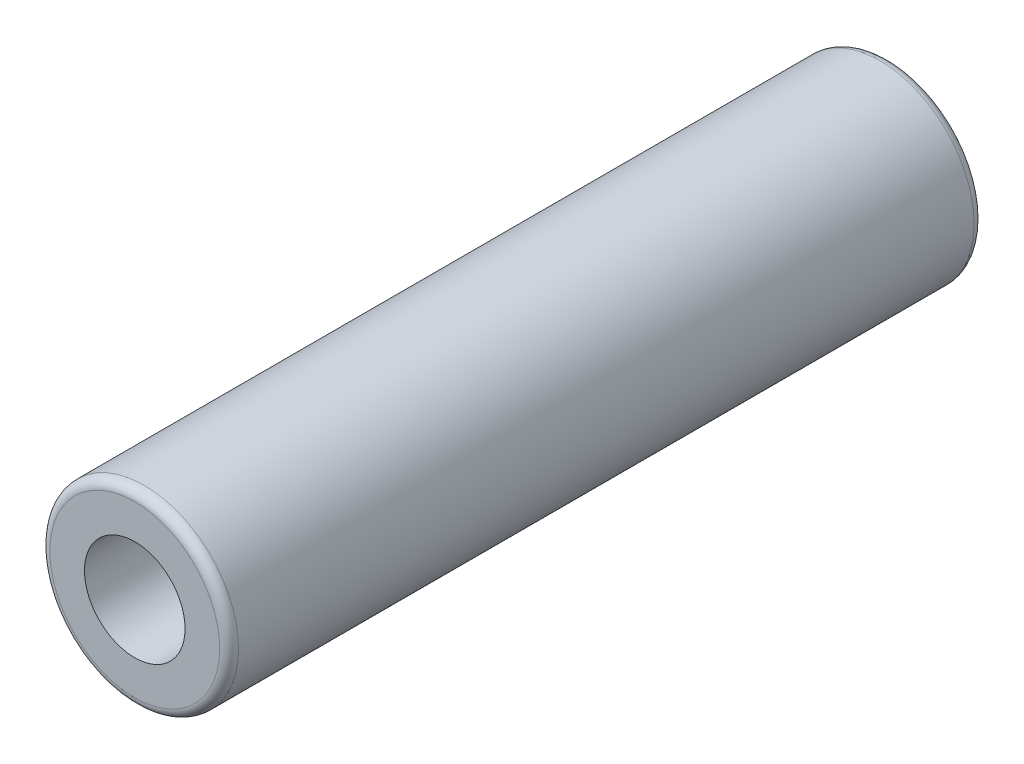
SolidWorks part; units mm, degrees
ref_plane "Front Plane" through (0, 0, 0) normal (0, 0, 1) x (1, 0, 0)
ref_plane "Top Plane" through (0, 0, 0) normal (0, 1, 0) x (1, 0, 0)
ref_plane "Right Plane" through (0, 0, 0) normal (1, 0, 0) x (0, 0, -1)
sketch "Sketch1" plane through (0, 0, 0) normal (0, 0, 1) x (1, 0, 0)
  circle A0 centre (0, 0) radius 3
  circle A1 centre (0, 0) radius 1.6
  dimension "D1" = 6
  dimension "D2" = 3.2
extrude "Boss-Extrude1" add sketch "Sketch1" along normal blind 24
fillet "Fillet1" radius 0.3 2 edges at (3, 0, 0) (3, 0, 24)
